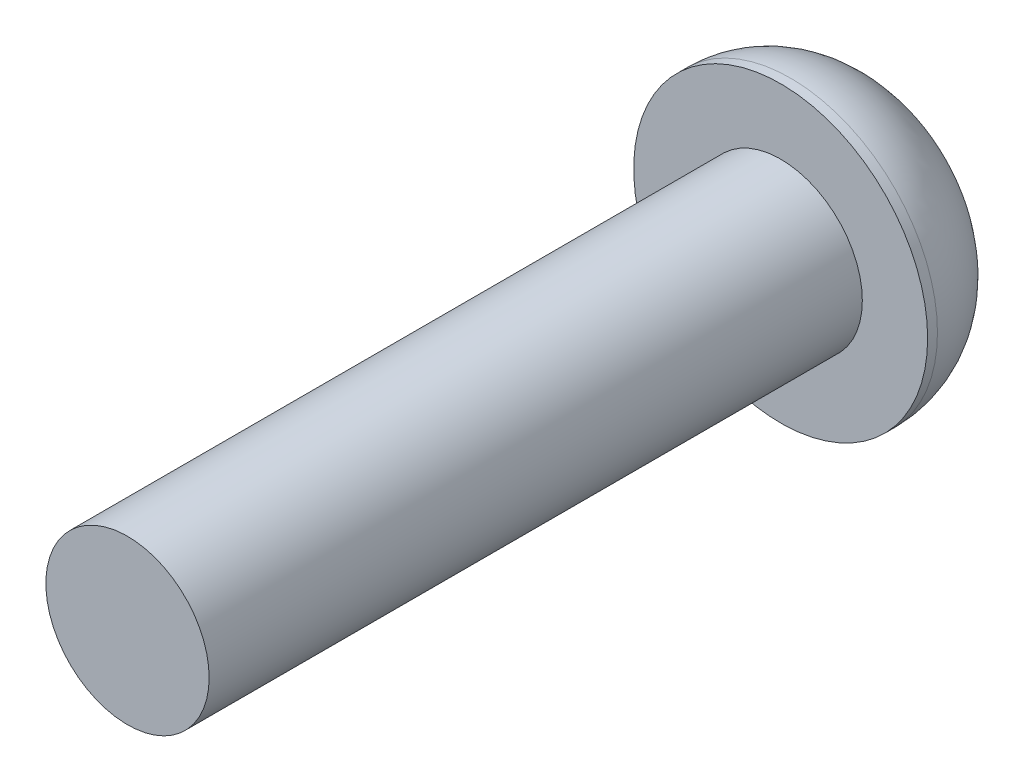
SolidWorks part; units mm, degrees
ref_plane "正面" through (0, 0, 0) normal (0, 0, 1) x (1, 0, 0)
ref_plane "平面" through (0, 0, 0) normal (0, 1, 0) x (1, 0, 0)
ref_plane "右側面" through (0, 0, 0) normal (1, 0, 0) x (0, 0, -1)
sketch "ｽｹｯﾁ1" plane through (0, 0, 0) normal (0, 0, 1) x (1, 0, 0)
  circle A0 centre (0, 0) radius 4.5
  dimension "D1" = 9
extrude "ﾎﾞｽ - 押し出し1" add sketch "ｽｹｯﾁ1" along normal blind 3.3
sketch "ｽｹｯﾁ2" plane through (0, 0, 3.3) normal (0, 0, 1) x (1, 0, 0)
  circle A0 centre (0, 0) radius 2.5
  dimension "D1" = 5
extrude "ﾎﾞｽ - 押し出し2" add sketch "ｽｹｯﾁ2" along normal blind 20
cosmetic thread "ねじ山1" parameters "D2"=4.11
fillet "ﾌｨﾚｯﾄ2" radius 3 1 edges at (4.5, 0, 0)
sketch "ｽｹｯﾁ3" plane through (0, 0, 0) normal (0, 0, -1) x (-1, 0, 0)
  line L1 (-3, -1) -> (3, -1)
  line L2 (-3, -1) -> (-3, 1)
  line L3 (-3, 1) -> (3, 1)
  line L4 (3, -1) -> (3, 1)
  line L5 (-3, -1) -> (3, 1) construction
  line L6 (-3, 1) -> (3, -1) construction
  line L7 (-1, -3) -> (1, -3)
  line L8 (-1, -3) -> (-1, 3)
  line L9 (-1, 3) -> (1, 3)
  line L10 (1, -3) -> (1, 3)
  line L11 (-1, -3) -> (1, 3) construction
  line L12 (-1, 3) -> (1, -3) construction
  point P0 (0, 0)
  point P5 (0, 0)
  circle M1 centre (0, 0) radius 1.5
  dimension "D1" = 2
  dimension "D2" = 2
  dimension "D3" = 6
  dimension "D4" = 6
extrude "ｶｯﾄ - 押し出し1" cut sketch "ｽｹｯﾁ3" against normal blind 3 contours L10 L9 L8 M1 | L1 L10 L3 L8 | L1 L4 L3 M1 | L10 L1 L3 M1 | L1 L8 L3 M1 | L3 L2 L1 M1 | L10 L1 L8 M1 | L7 L10 L8 M1 | L3 L10 L8 M1
